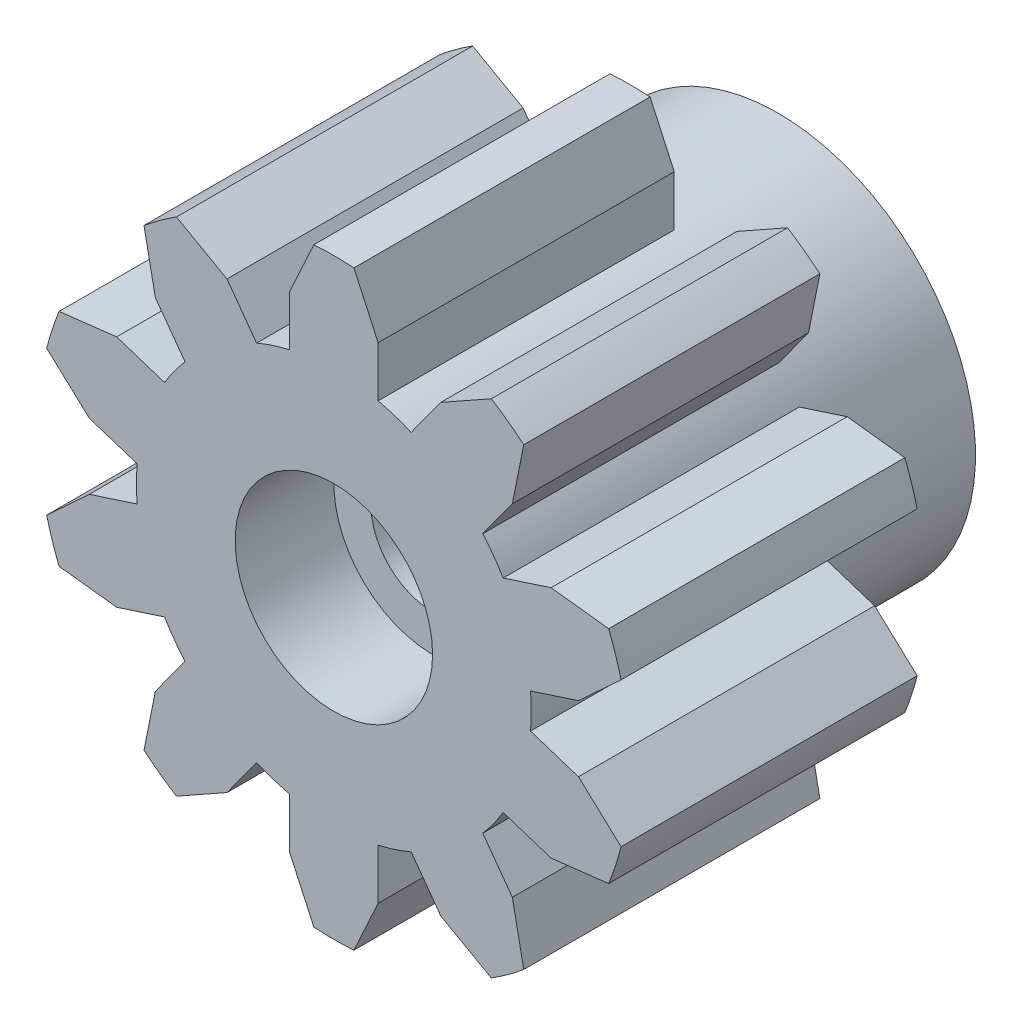
SolidWorks part; units mm, degrees
ref_plane "前视基准面" through (0, 0, 0) normal (0, 0, 1) x (1, 0, 0)
ref_plane "上视基准面" through (0, 0, 0) normal (0, 1, 0) x (1, 0, 0)
ref_plane "右视基准面" through (0, 0, 0) normal (1, 0, 0) x (0, 0, -1)
ref_plane "基准面1" through (0, 0, 0) normal (0, -1, 0) x (1, 0, 0)
sketch "草图1" plane through (0, 0, 0) normal (0, -1, 0) x (1, 0, 0)
  line L0 (4, 6) -> (0, 6)
  line L1 (0, 6) -> (0, -3)
  line L2 (0, -3) -> (4, -3)
  line L3 (4, -3) -> (4, 6)
  line L4 (0, 6) -> (0, -3) construction
  dimension "D1" = 4
  dimension "D2" = 9
revolve "旋转1" add sketch "草图1" angle 360 about L4
ref_plane "基准面2" through (0, 0, 6) normal (0, 0, 1) x (1, 0, 0)
sketch "草图2" plane through (0, 0, 6) normal (0, 0, 1) x (1, 0, 0)
  line L0 (3.9845, 0.3522) -> (4.9552, 0.6676)
  line L1 (4.9552, 0.6676) -> (5.8188, 1.4634)
  line L2 (5.5677, 2.2363) -> (4.4013, 2.3725)
  line L3 (4.4013, 2.3725) -> (3.4305, 2.0571)
  arc A0 (3.4305, 2.0571) -> (3.9845, 0.3522) centre (0, 0) cw
  arc A1 (5.8188, 1.4634) -> (5.5677, 2.2363) centre (0, 0) ccw
  dimension "D1" = 4
  dimension "D2" = 6
  dimension "D3" = 0.2511
  dimension "D4" = 0.8636
  dimension "D5" = 1.4175
  dimension "D6" = 1.8343
  dimension "D7" = 2.3883
  dimension "D8" = 5.8188
  dimension "D9" = 0.1362
  dimension "D10" = 1.705
extrude "凸台-拉伸1" add sketch "草图2" against normal blind 6
sketch "草图3" plane through (0, 0, 6) normal (0, 0, 1) x (1, 0, 0)
  line L0 (3.0165, 2.6269) -> (3.6165, 3.4527)
  line L1 (3.6165, 3.4527) -> (3.8473, 4.6041)
  line L2 (3.1899, 5.0818) -> (2.1662, 4.5064)
  line L3 (2.1662, 4.5064) -> (1.5662, 3.6806)
  arc A0 (1.5662, 3.6806) -> (3.0165, 2.6269) centre (0, 0) cw
  arc A1 (3.8473, 4.6041) -> (3.1899, 5.0818) centre (0, 0) ccw
  dimension "D1" = 4
  dimension "D2" = 6
  dimension "D3" = 0.2309
  dimension "D4" = 0.6574
  dimension "D5" = 0.8308
  dimension "D6" = 1.6812
  dimension "D7" = 2.2811
  dimension "D8" = 3.8473
  dimension "D9" = 0.5754
  dimension "D10" = 1.6291
extrude "凸台-拉伸2" add sketch "草图3" against normal blind 6
sketch "草图4" plane through (0, 0, 6) normal (0, 0, 1) x (1, 0, 0)
  line L0 (0.8963, 3.8983) -> (0.8963, 4.919)
  line L1 (0.8963, 4.919) -> (0.4063, 5.9862)
  line L2 (-0.4063, 5.9862) -> (-0.8963, 4.919)
  line L3 (-0.8963, 4.919) -> (-0.8963, 3.8983)
  arc A0 (-0.8963, 3.8983) -> (0.8963, 3.8983) centre (0, 0) cw
  arc A1 (0.4063, 5.9862) -> (-0.4063, 5.9862) centre (0, 0) ccw
  dimension "D1" = 4
  dimension "D2" = 6
  dimension "D3" = 0.49
  dimension "D4" = 0.8963
  dimension "D5" = 4.919
extrude "凸台-拉伸3" add sketch "草图4" against normal blind 6
sketch "草图5" plane through (0, 0, 6) normal (0, 0, 1) x (1, 0, 0)
  line L0 (-1.5662, 3.6806) -> (-2.1662, 4.5064)
  line L1 (-2.1662, 4.5064) -> (-3.1899, 5.0818)
  line L2 (-3.8473, 4.6041) -> (-3.6165, 3.4527)
  line L3 (-3.6165, 3.4527) -> (-3.0165, 2.6269)
  arc A0 (-3.0165, 2.6269) -> (-1.5662, 3.6806) centre (0, 0) cw
  arc A1 (-3.1899, 5.0818) -> (-3.8473, 4.6041) centre (0, 0) ccw
  dimension "D1" = 4
  dimension "D2" = 6
  dimension "D3" = 1.5662
  dimension "D4" = 2.1662
  dimension "D5" = 3.0165
  dimension "D6" = 3.1899
  dimension "D7" = 3.6165
  dimension "D8" = 3.8473
  dimension "D9" = 0.5754
  dimension "D10" = 1.6291
extrude "凸台-拉伸4" add sketch "草图5" against normal blind 6
sketch "草图6" plane through (0, 0, 6) normal (0, 0, 1) x (1, 0, 0)
  line L0 (-3.4305, 2.0571) -> (-4.4013, 2.3725)
  line L1 (-4.4013, 2.3725) -> (-5.5677, 2.2363)
  line L2 (-5.8188, 1.4634) -> (-4.9552, 0.6676)
  line L3 (-4.9552, 0.6676) -> (-3.9845, 0.3522)
  arc A0 (-3.9845, 0.3522) -> (-3.4305, 2.0571) centre (0, 0) cw
  arc A1 (-5.5677, 2.2363) -> (-5.8188, 1.4634) centre (0, 0) ccw
  dimension "D1" = 4
  dimension "D2" = 6
  dimension "D3" = 3.4305
  dimension "D4" = 3.9845
  dimension "D5" = 4.4013
  dimension "D6" = 4.9552
  dimension "D7" = 5.5677
  dimension "D8" = 5.8188
  dimension "D9" = 0.1362
  dimension "D10" = 1.705
extrude "凸台-拉伸5" add sketch "草图6" against normal blind 6
sketch "草图7" plane through (0, 0, 6) normal (0, 0, 1) x (1, 0, 0)
  line L0 (-3.9845, -0.3522) -> (-4.9552, -0.6676)
  line L1 (-4.9552, -0.6676) -> (-5.8188, -1.4634)
  line L2 (-5.5677, -2.2363) -> (-4.4013, -2.3725)
  line L3 (-4.4013, -2.3725) -> (-3.4305, -2.0571)
  arc A0 (-3.4305, -2.0571) -> (-3.9845, -0.3522) centre (0, 0) cw
  arc A1 (-5.8188, -1.4634) -> (-5.5677, -2.2363) centre (0, 0) ccw
  dimension "D1" = 4
  dimension "D2" = 6
  dimension "D3" = 3.4305
  dimension "D4" = 3.9845
  dimension "D5" = 4.4013
  dimension "D6" = 4.9552
  dimension "D7" = 5.5677
  dimension "D8" = 5.8188
  dimension "D9" = 0.6676
  dimension "D10" = 2.3725
extrude "凸台-拉伸6" add sketch "草图7" against normal blind 6
sketch "草图8" plane through (0, 0, 6) normal (0, 0, 1) x (1, 0, 0)
  line L0 (-3.0165, -2.6269) -> (-3.6165, -3.4527)
  line L1 (-3.6165, -3.4527) -> (-3.8473, -4.6041)
  line L2 (-3.1899, -5.0818) -> (-2.1662, -4.5064)
  line L3 (-2.1662, -4.5064) -> (-1.5662, -3.6806)
  arc A0 (-1.5662, -3.6806) -> (-3.0165, -2.6269) centre (0, 0) cw
  arc A1 (-3.8473, -4.6041) -> (-3.1899, -5.0818) centre (0, 0) ccw
  dimension "D1" = 4
  dimension "D2" = 6
  dimension "D3" = 1.5662
  dimension "D4" = 2.1662
  dimension "D5" = 3.0165
  dimension "D6" = 3.1899
  dimension "D7" = 3.6165
  dimension "D8" = 3.8473
  dimension "D9" = 3.4527
  dimension "D10" = 4.5064
extrude "凸台-拉伸7" add sketch "草图8" against normal blind 6
sketch "草图9" plane through (0, 0, 6) normal (0, 0, 1) x (1, 0, 0)
  line L0 (-0.8963, -3.8983) -> (-0.8963, -4.919)
  line L1 (-0.8963, -4.919) -> (-0.4063, -5.9862)
  line L2 (0.4063, -5.9862) -> (0.8963, -4.919)
  line L3 (0.8963, -4.919) -> (0.8963, -3.8983)
  arc A0 (0.8963, -3.8983) -> (-0.8963, -3.8983) centre (0, 0) cw
  arc A1 (-0.4063, -5.9862) -> (0.4063, -5.9862) centre (0, 0) ccw
  dimension "D1" = 4
  dimension "D2" = 6
  dimension "D3" = 0.49
  dimension "D4" = 0.8963
  dimension "D5" = 1.0672
extrude "凸台-拉伸8" add sketch "草图9" against normal blind 6
sketch "草图10" plane through (0, 0, 6) normal (0, 0, 1) x (1, 0, 0)
  line L0 (1.5662, -3.6806) -> (2.1662, -4.5064)
  line L1 (2.1662, -4.5064) -> (3.1899, -5.0818)
  line L2 (3.8473, -4.6041) -> (3.6165, -3.4527)
  line L3 (3.6165, -3.4527) -> (3.0165, -2.6269)
  arc A0 (3.0165, -2.6269) -> (1.5662, -3.6806) centre (0, 0) cw
  arc A1 (3.1899, -5.0818) -> (3.8473, -4.6041) centre (0, 0) ccw
  dimension "D1" = 4
  dimension "D2" = 6
  dimension "D3" = 0.2309
  dimension "D4" = 0.6574
  dimension "D5" = 0.8308
  dimension "D6" = 1.6812
  dimension "D7" = 2.2811
  dimension "D8" = 3.8473
  dimension "D9" = 3.4527
  dimension "D10" = 4.5064
extrude "凸台-拉伸9" add sketch "草图10" against normal blind 6
sketch "草图11" plane through (0, 0, 6) normal (0, 0, 1) x (1, 0, 0)
  line L0 (3.4305, -2.0571) -> (4.4013, -2.3725)
  line L1 (4.4013, -2.3725) -> (5.5677, -2.2363)
  line L2 (5.8188, -1.4634) -> (4.9552, -0.6676)
  line L3 (4.9552, -0.6676) -> (3.9845, -0.3522)
  arc A0 (3.9845, -0.3522) -> (3.4305, -2.0571) centre (0, 0) cw
  arc A1 (5.5677, -2.2363) -> (5.8188, -1.4634) centre (0, 0) ccw
  dimension "D1" = 4
  dimension "D2" = 6
  dimension "D3" = 0.2511
  dimension "D4" = 0.8636
  dimension "D5" = 1.4175
  dimension "D6" = 1.8343
  dimension "D7" = 2.3883
  dimension "D8" = 5.8188
  dimension "D9" = 0.6676
  dimension "D10" = 2.3725
extrude "凸台-拉伸10" add sketch "草图11" against normal blind 6
hole_wizard "M2 六角头机械螺钉的柱形沉头孔1" positions "草图13" profile "草图12" counterbore size "M2" standard "ANSI Metric"
sketch "草图13" plane through (0, 0, 6) normal (0, 0, 1) x (1, 0, 0)
  point P0 (0, 0)
sketch "草图12" plane through (0, 0, 6) normal (1, 0, 0) x (0, -1, 0)
  line L0 (0, 0) -> (0, 9)
  line L1 (0, 9) -> (1.25, 9)
  line L3 (1.25, 9) -> (1.25, 2)
  line L4 (1.25, 2) -> (2, 2)
  line L5 (2, 2) -> (2, 0)
  line L7 (2, 0) -> (0, 0)
  line L11 (0, -6.35) -> (0, 107.95) construction
  dimension "通孔孔直径" = 2.5
  dimension "通孔孔深度" = 9
  dimension "柱形沉头孔直径" = 4
  dimension "柱形沉头孔深度" = 2
